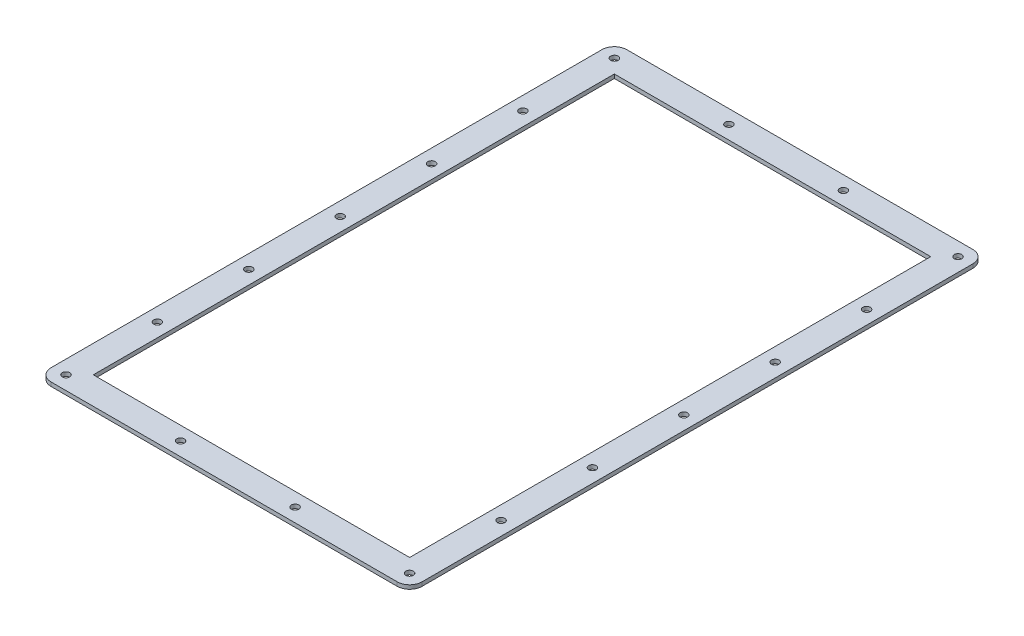
SolidWorks part; units mm, degrees
material "5052-H32"
ref_plane "Front Plane" through (0, 0, 0) normal (0, 0, 1) x (1, 0, 0)
ref_plane "Top Plane" through (0, 0, 0) normal (0, 1, 0) x (1, 0, 0)
ref_plane "Right Plane" through (0, 0, 0) normal (1, 0, 0) x (0, 0, -1)
sketch "Sketch1" plane through (0, 0, 0) normal (0, 1, 0) x (1, 0, 0)
  line L0 (-147, 192) -> (152, 192)
  line L1 (-125, -250) -> (130, -250)
  line L2 (-125, -250) -> (-125, 170)
  line L3 (-125, 170) -> (130, 170)
  line L4 (130, -250) -> (130, 170)
  line L5 (-125, -250) -> (130, 170) construction
  line L6 (-125, 170) -> (130, -250) construction
  line L7 (152, -272) -> (152, 192)
  line L8 (-147, -272) -> (152, -272)
  line L9 (-147, -272) -> (-147, 192)
  line L12 (130, -40) -> (-125, -40) construction
  circle A34 centre (141, 181) radius 3
  circle A35 centre (48.6667, 181) radius 3
  circle A36 centre (-43.6667, 181) radius 3
  circle A37 centre (-136, 181) radius 3
  circle A90 centre (141, 107.3333) radius 3
  circle A91 centre (141, 33.6667) radius 3
  circle A92 centre (141, -40) radius 3
  circle A93 centre (141, -113.6667) radius 3
  circle A94 centre (141, -187.3333) radius 3
  circle A102 centre (-136, 107.3333) radius 3
  circle A103 centre (141, -261) radius 3
  circle A106 centre (-136, 33.6667) radius 3
  circle A107 centre (48.6667, -261) radius 3
  circle A110 centre (-136, -40) radius 3
  circle A111 centre (-43.6667, -261) radius 3
  circle A114 centre (-136, -113.6667) radius 3
  circle A115 centre (-136, -261) radius 3
  circle A118 centre (-136, -187.3333) radius 3
  circle A119 centre (48.6667, -113.6667) radius 3 [skipped]
  circle A120 centre (-43.6667, -113.6667) radius 3 [skipped]
  circle A121 centre (48.6667, 107.3333) radius 3 [skipped]
  circle A122 centre (-43.6667, 107.3333) radius 3 [skipped]
  circle A123 centre (48.6667, 33.6667) radius 3 [skipped]
  circle A124 centre (48.6667, -40) radius 3 [skipped]
  circle A125 centre (-43.6667, -40) radius 3 [skipped]
  circle A126 centre (-43.6667, 33.6667) radius 3 [skipped]
  circle A127 centre (48.6667, -187.3333) radius 3 [skipped]
  circle A128 centre (-43.6667, -187.3333) radius 3 [skipped]
  dimension "D2" = 420
  dimension "D1" = 22
  dimension "D3" = 255
  dimension "D5" = 11
  dimension "D6" = 11
  dimension "D9" = 73.6667
  dimension "D10" = 92.3333
  dimension "D7" = 4
  dimension "D8" = 7
extrude "Boss-Extrude1" add sketch "Sketch1" along normal blind 3.175
fillet "Fillet1" radius 10 4 edges at (152, 1.5875, 272) (-147, 1.5875, 272) (152, 1.5875, -192) (-147, 1.5875, -192)
equation "\"L\"= 420mm"
equation "\"W\"= 255mm"
equation "\"H\"= 110mm"
equation "\"Compartment Width\"= 80"
equation "\"T\"= 4.7625 * 2 / 3mm"
equation "\"Inside Fillet Radius\"= 5.55625mm"
equation "\"Hole\"=25mm"
equation "\"D2@Sketch1\"=\"L\""
equation "\"D1@Boss-Extrude1\"=\"T\""
equation "\"D3@Sketch1\"=\"W\""
equation "\"D9@Sketch1\"=(\"L\"+22)/6"
equation "\"D10@Sketch1\"=(\"W\"+22)/3"
equation "\"Offset\"= 18mm"
equation "\"Wheel to Wall\"= 43"
